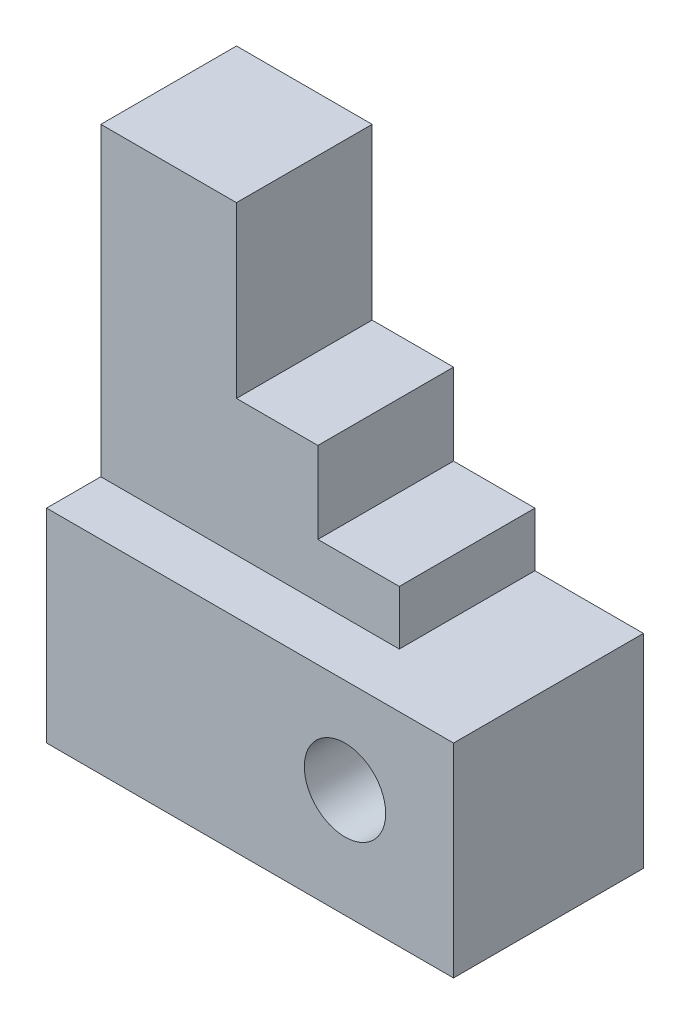
SolidWorks part; units mm, degrees
material "Aluminum Bronze"
ref_plane "Front Plane" through (0, 0, 0) normal (0, 0, 1) x (1, 0, 0)
ref_plane "Top Plane" through (0, 0, 0) normal (0, 1, 0) x (1, 0, 0)
ref_plane "Right Plane" through (0, 0, 0) normal (1, 0, 0) x (0, 0, -1)
sketch "Sketch1" plane through (0, 0, 0) normal (0, 0, 1) x (1, 0, 0)
  line L1 (0, 0) -> (60, 0)
  line L2 (0, 0) -> (0, 30)
  line L3 (0, 30) -> (60, 30)
  line L4 (60, 0) -> (60, 30)
  circle A0 centre (44, 16) radius 6
  dimension "D2" = 16
  dimension "D3" = 12
  dimension "D1" = 30
  dimension "D4" = 44
  dimension "D5" = 60
extrude "Boss-Extrude1" add sketch "Sketch1" along normal blind 28
sketch "Sketch3" plane through (0, 0, 0) normal (0, 0, 1) x (1, 0, 0)
  line L0 (0, 30) -> (0, 75)
  line L1 (0, 75) -> (20, 75)
  line L2 (20, 75) -> (20, 50)
  line L3 (20, 50) -> (32, 50)
  line L4 (32, 50) -> (32, 38)
  line L5 (32, 38) -> (44, 38)
  line L6 (44, 38) -> (44, 30)
  line L7 (60, 30) -> (0, 30) construction
  line L8 (0, 30) -> (44, 30)
  line L9 (0, 0) -> (60, 0) construction
  point P14 (44, 38.6121)
  dimension "D1" = 75
  dimension "D2" = 20
  dimension "D3" = 12
  dimension "D4" = 20
  dimension "D5" = 12
  dimension "D6" = 12
extrude "Boss-Extrude2" add sketch "Sketch3" along normal blind 20
